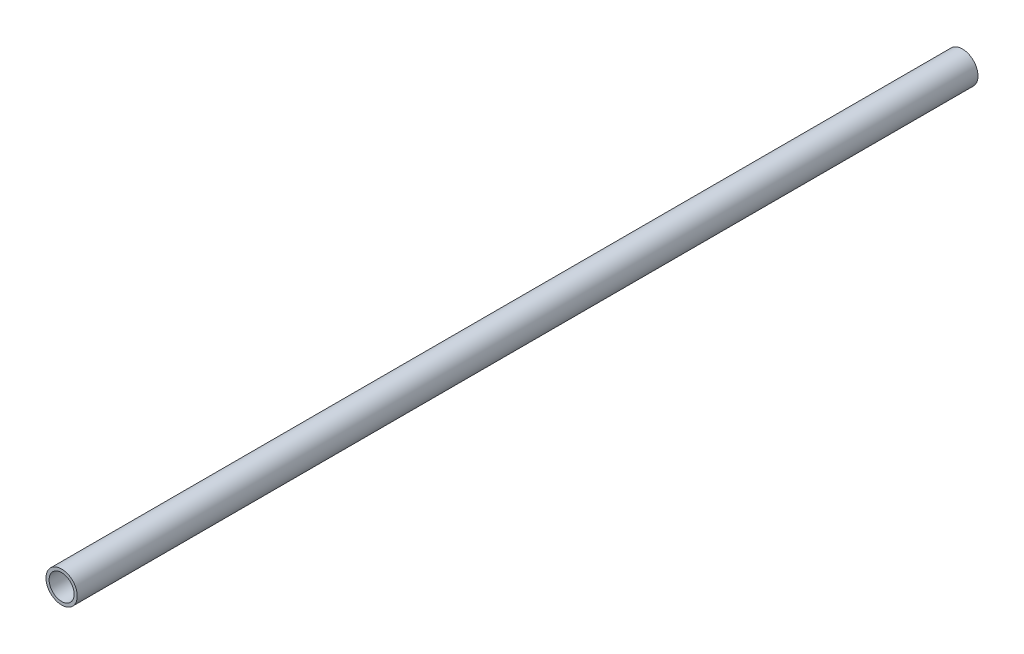
SolidWorks part; units mm, degrees
ref_plane "Front Plane" through (0, 0, 0) normal (0, 0, 1) x (1, 0, 0)
ref_plane "Top Plane" through (0, 0, 0) normal (0, 1, 0) x (1, 0, 0)
ref_plane "Right Plane" through (0, 0, 0) normal (1, 0, 0) x (0, 0, -1)
sketch "Sketch1" plane through (0, 0, 0) normal (0, 0, 1) x (1, 0, 0)
  line L0 (-15.875, 0) -> (15.875, 0) construction
  line L1 (0, -15.875) -> (0, 15.875) construction
  circle A0 centre (0, 0) radius 15.875
  circle A1 centre (0, 0) radius 12.7
  point P4 (0, 0)
  point P9 (0, 0)
  point P10 (12.7, 0)
  dimension "ID" = 25.4
  dimension "OD" = 31.75
  dimension "Wall Thickness" = 3.175
sketch "Sketch2" plane through (0, 0, 0) normal (1, 0, 0) x (0, 0, -1)
  line L0 (457.2, 15.875) -> (-457.2, 15.875) construction
  line L1 (0, 15.875) -> (0, -15.875) construction
  point P3 (-381, 15.875)
  point P4 (0, 15.875)
  point P5 (381, 15.875)
  dimension "D1" = 76.2
  dimension "D2" = 76.2
  dimension "Length" = 914.4
sketch "Sketch3" plane through (0, 0, 0) normal (0, 0, 1) x (1, 0, 0)
  line L0 (0, -15.875) -> (0, 15.875) construction
  circle A0 centre (0, 0) radius 15.875
  circle A1 centre (0, 0) radius 12.7
  circle A2 centre (0, 0) radius 12.7 construction
extrude "Boss-Extrude1" add sketch "Sketch3" along normal mid plane 914.4
equation "\"D1@Boss-Extrude1\" = \"Length@Sketch2\""
equation "\"D2@Sketch2\"=\"D1@Sketch2\""
